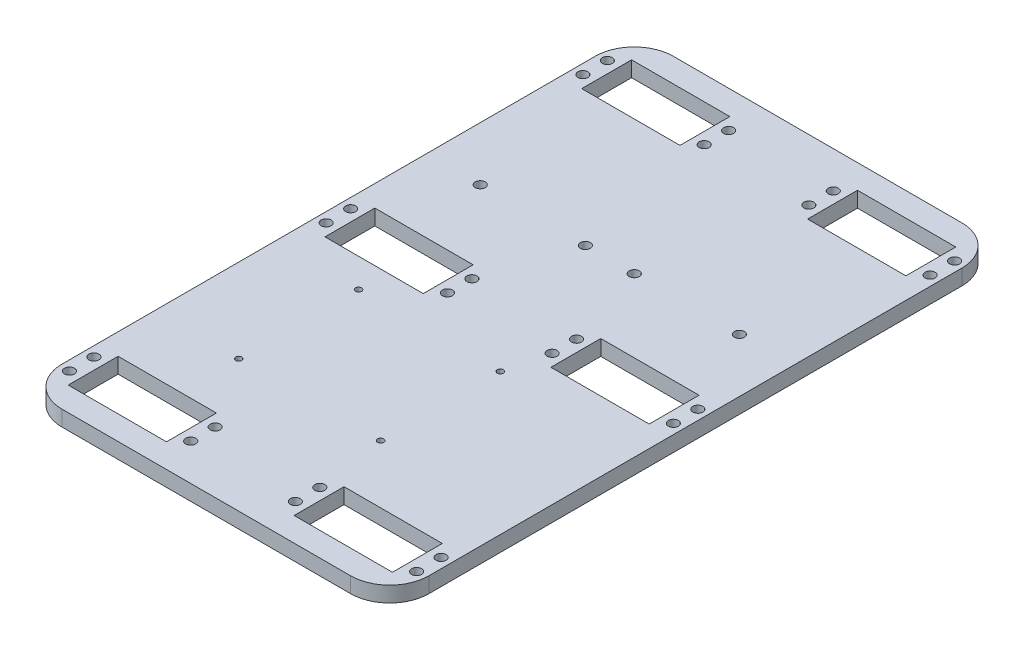
SolidWorks part; units mm, degrees
ref_plane "Front Plane" through (0, 0, 0) normal (0, 0, 1) x (1, 0, 0)
ref_plane "Top Plane" through (0, 0, 0) normal (0, 1, 0) x (1, 0, 0)
ref_plane "Right Plane" through (0, 0, 0) normal (1, 0, 0) x (0, 0, -1)
sketch "Sketch1" plane through (0, 0, 0) normal (0, 1, 0) x (1, 0, 0)
  line L0 (0, 125) -> (0, -125) construction
  line L1 (-75, 125) -> (75, 125)
  line L2 (-75, 125) -> (-75, -125)
  line L3 (-75, -125) -> (75, -125)
  line L4 (75, 125) -> (75, -125)
  line L5 (-75, 125) -> (75, -125) construction
  line L6 (-75, -125) -> (75, 125) construction
  line L7 (-75, 0) -> (75, 0) construction
  line L8 (75, -125) -> (-75, 125) construction
  line L9 (75, 125) -> (-75, -125) construction
  line L10 (-46.2, 125) -> (-46.2, -125) construction
  line L11 (-71, -100) -> (-71, -110) construction
  line L12 (-40.75, -22) -> (17.25, -22) construction
  line L13 (-40.75, -22) -> (-40.75, -71) construction
  line L14 (-40.75, -71) -> (17.25, -71) construction
  line L15 (17.25, -22) -> (17.25, -71) construction
  line L16 (-40.75, -22) -> (40.75, -22) construction
  line L17 (-40.75, -22) -> (-40.75, -71) construction
  line L18 (-40.75, -71) -> (40.75, -71) construction
  line L19 (40.75, -22) -> (40.75, -71) construction
  line L20 (-66.3, -94.8) -> (-26.1, -94.8)
  line L21 (-66.3, -94.8) -> (-66.3, -115.2)
  line L22 (-66.3, -115.2) -> (-26.1, -115.2)
  line L23 (-26.1, -94.8) -> (-26.1, -115.2)
  line L24 (66.3, -94.8) -> (66.3, -115.2)
  line L25 (66.3, -94.8) -> (26.1, -94.8)
  line L26 (26.1, -94.8) -> (26.1, -115.2)
  line L27 (66.3, -115.2) -> (26.1, -115.2)
  line L28 (-26.1, 94.8) -> (-26.1, 115.2)
  line L29 (-66.3, 115.2) -> (-26.1, 115.2)
  line L30 (-66.3, 94.8) -> (-66.3, 115.2)
  line L31 (-66.3, 94.8) -> (-26.1, 94.8)
  line L32 (66.3, 115.2) -> (26.1, 115.2)
  line L33 (26.1, 94.8) -> (26.1, 115.2)
  line L34 (66.3, 94.8) -> (26.1, 94.8)
  line L35 (66.3, 94.8) -> (66.3, 115.2)
  line L36 (-71, 5) -> (-71, -5) construction
  line L37 (-66.3, 10.2) -> (-26.1, 10.2)
  line L38 (-66.3, 10.2) -> (-66.3, -10.2)
  line L39 (-66.3, -10.2) -> (-26.1, -10.2)
  line L40 (-26.1, 10.2) -> (-26.1, -10.2)
  line L41 (26.1, 10.2) -> (26.1, -10.2)
  line L42 (66.3, -10.2) -> (26.1, -10.2)
  line L43 (66.3, 10.2) -> (66.3, -10.2)
  line L44 (66.3, 10.2) -> (26.1, 10.2)
  circle A0 centre (-71, 5) radius 2.05
  circle A1 centre (-71, -5) radius 2.05
  circle A12 centre (-71, -100) radius 2.05
  circle A13 centre (-71, -110) radius 2.05
  circle A14 centre (-71, 110) radius 2.05
  circle A15 centre (-71, 100) radius 2.05
  circle A22 centre (-21.4, 100) radius 2.05
  circle A23 centre (-21.4, 110) radius 2.05
  circle A24 centre (-21.4, -110) radius 2.05
  circle A25 centre (-21.4, -100) radius 2.05
  circle A26 centre (-21.4, -5) radius 2.05
  circle A27 centre (-21.4, 5) radius 2.05
  circle A28 centre (21.4, 5) radius 2.05
  circle A29 centre (21.4, -5) radius 2.05
  circle A30 centre (21.4, -100) radius 2.05
  circle A31 centre (21.4, -110) radius 2.05
  circle A32 centre (21.4, 110) radius 2.05
  circle A33 centre (21.4, 100) radius 2.05
  circle A34 centre (71, 100) radius 2.05
  circle A35 centre (71, 110) radius 2.05
  circle A36 centre (71, -110) radius 2.05
  circle A37 centre (71, -100) radius 2.05
  circle A38 centre (71, -5) radius 2.05
  circle A39 centre (71, 5) radius 2.05
  circle A40 centre (-40.75, -22) radius 1.25
  circle A41 centre (-40.75, -71) radius 1.25
  circle A42 centre (17.25, -71) radius 1.25
  circle A43 centre (17.25, -22) radius 1.25
  circle A44 centre (-53, 40) radius 2.05
  circle A45 centre (-10, 40) radius 2.05
  circle A46 centre (10, 40) radius 2.05
  circle A47 centre (53, 40) radius 2.05
  point P11 (0, 0)
  point P74 (-71, -105)
  point P75 (-66.3, -105)
  point P76 (-71, 0)
  point P93 (-66.3, 105)
  point P102 (-66.3, 0)
  point P103 (0, 0)
  point P108 (66.3, 0)
  dimension "D5" = 4.1
  dimension "D11" = 2.5
  dimension "D17" = 4.1
  dimension "D1" = 250
  dimension "D6" = 10
  dimension "D7" = 4
  dimension "D9" = 150
  dimension "D2" = 5
  dimension "D3" = 10
  dimension "D4" = 4
  dimension "D8" = 15
  dimension "D10" = 24.8
  dimension "D12" = 58
  dimension "D13" = 49
  dimension "D14" = 23.5
  dimension "D15" = 22
  dimension "D16" = 40.75
  dimension "D18" = 43
  dimension "D19" = 10
  dimension "D20" = 40
  dimension "D21" = 20.4
  dimension "D22" = 4.7
  dimension "D23" = 40.2
  dimension "D24" = 4.7
  dimension "D25" = 40.2
  dimension "D26" = 20.4
extrude "Boss-Extrude1" add sketch "Sketch1" along normal blind 6.35
fillet "Fillet1" radius 16 4 edges at (-75, 3.175, -125) (75, 3.175, -125) (75, 3.175, 125) (-75, 3.175, 125)
equation "\"D4@Sketch1\"=\"D7@Sketch1\""
